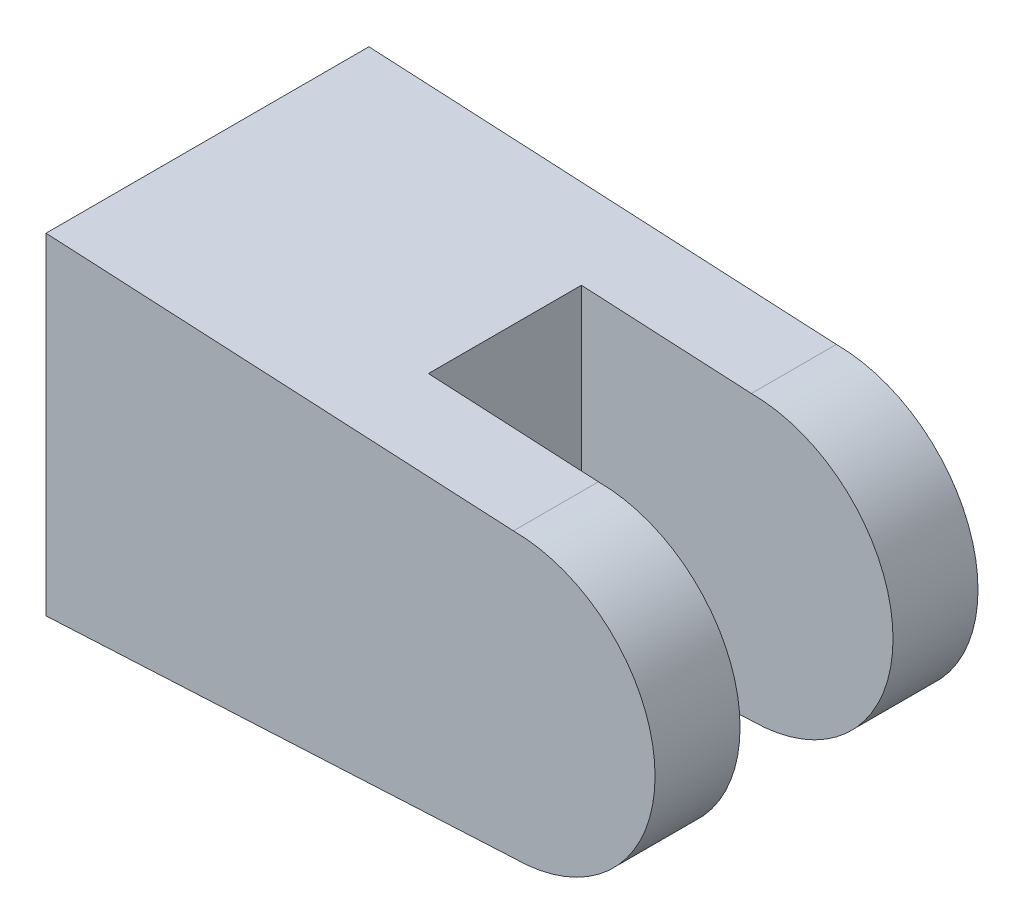
SolidWorks part; units mm, degrees
ref_plane "Front Plane" through (0, 0, 0) normal (0, 0, 1) x (1, 0, 0)
ref_plane "Top Plane" through (0, 0, 0) normal (0, 1, 0) x (1, 0, 0)
ref_plane "Right Plane" through (0, 0, 0) normal (1, 0, 0) x (0, 0, -1)
sketch "Sketch1" plane through (0, 0, 0) normal (0, 0, 1) x (1, 0, 0)
  line L0 (0, 0) -> (-235.0753, 0) construction
  line L1 (0, 50) -> (-165, 58.5)
  line L2 (-165, 58.5) -> (-165, -58.5)
  line L3 (0, -50) -> (-165, -58.5)
  arc A0 (0, -50) -> (0, 50) centre (0, 0) ccw
  point P8 (-165, 0)
  dimension "D1" = 165
  dimension "D2" = 100
  dimension "D3" = 58.5
extrude "Boss-Extrude1" add sketch "Sketch1" along normal mid plane 114
sketch "Sketch2" plane through (-165, 0, 0) normal (-1, 0, 0) x (0, 0, 1)
  circle A0 centre (0, 0) radius 37.5
  dimension "D1" = 75
extrude "Boss-Extrude2" add sketch "Sketch2" along normal blind 2
sketch "Sketch3" plane through (0, 0, 0) normal (0, 1, 0) x (1, 0, 0)
  line L0 (50, -57) -> (50, 57) construction
  line L1 (50, 27) -> (-60, 27)
  line L2 (50, 27) -> (50, -27)
  line L3 (50, -27) -> (-60, -27)
  line L4 (-60, 27) -> (-60, -27)
  point P6 (50, 0)
  dimension "D1" = 54
  dimension "D2" = 110
extrude "Cut-Extrude2" cut sketch "Sketch3" against normal through all both and the other way through all
